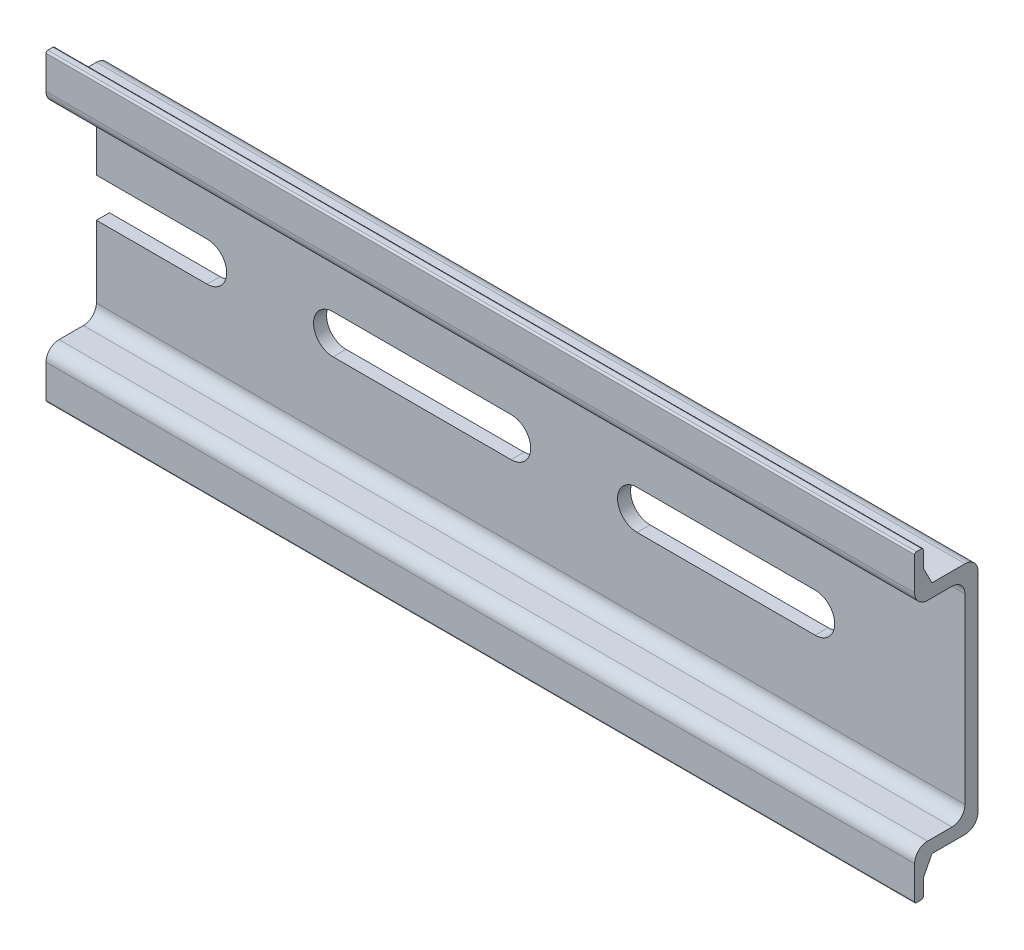
SolidWorks part; units mm, degrees
ref_plane "Front Plane" through (0, 0, 0) normal (0, 0, 1) x (1, 0, 0)
ref_plane "Top Plane" through (0, 0, 0) normal (0, 1, 0) x (1, 0, 0)
ref_plane "Right Plane" through (0, 0, 0) normal (1, 0, 0) x (0, 0, -1)
sketch "Sketch1" plane through (0, 0, 0) normal (1, 0, 0) x (0, 0, -1)
  line L0 (-6.5, 17.5) -> (-7.1, 17.5)
  line L1 (-7.3, 17.3) -> (-7.3, 13.5)
  line L2 (-5.8, 12) -> (-3, 12)
  line L3 (-1.5, 10.5) -> (-1.5, -10.5)
  line L4 (-5.8, -12) -> (-3, -12)
  line L5 (-6.3, -15.4626) -> (-6.3, -17.3)
  line L6 (-5.3, -13.5) -> (-6.3, -15.4626)
  line L7 (-1.5, -13.5) -> (-5.3, -13.5)
  line L8 (-7.3, -17.3) -> (-7.3, -13.5)
  line L9 (-6.5, -17.5) -> (-7.1, -17.5)
  line L10 (0, -12) -> (0, 12)
  line L11 (-1.5, 13.5) -> (-5.3, 13.5)
  line L12 (-5.3, 13.5) -> (-6.3, 15.4626)
  line L13 (-6.3, 15.4626) -> (-6.3, 17.3)
  line L14 (0, 0) -> (-7.3, 0) construction
  arc A0 (-6.3, 17.3) -> (-6.5, 17.5) centre (-6.5, 17.3) ccw
  arc A1 (-7.1, 17.5) -> (-7.3, 17.3) centre (-7.1, 17.3) ccw
  arc A2 (-7.3, 13.5) -> (-5.8, 12) centre (-5.8, 13.5) ccw
  arc A3 (-1.5, 10.5) -> (-3, 12) centre (-3, 10.5) ccw
  arc A4 (-1.5, -10.5) -> (-3, -12) centre (-3, -10.5) cw
  arc A5 (0, -12) -> (-1.5, -13.5) centre (-1.5, -12) cw
  arc A6 (-7.3, -13.5) -> (-5.8, -12) centre (-5.8, -13.5) cw
  arc A7 (-7.1, -17.5) -> (-7.3, -17.3) centre (-7.1, -17.3) cw
  arc A8 (-6.3, -17.3) -> (-6.5, -17.5) centre (-6.5, -17.3) cw
  arc A9 (0, 12) -> (-1.5, 13.5) centre (-1.5, 12) ccw
  dimension "FIX_9" = 1.5
  dimension "FIX_10" = 1.5
  dimension "FIX_11" = 0.2
  dimension "FIX_12" = 0.2
  dimension "FIX_13" = 1.5
  dimension "FIX_1" = 35
  dimension "FIX_2" = 24
  dimension "FIX_3" = 7.3
  dimension "FIX_4" = 27
  dimension "FIX_5" = 1
  dimension "FIX_6" = 5.3
  dimension "FIX_7" = 117
  dimension "FIX_8" = 1.5
extrude "Boss-Extrude1" add sketch "Sketch1" along normal blind 100
ref_plane "Plane1" through (100, 0, 0) normal (1, 0, 0) x (0, 0, -1)
sketch "Sketch2" plane through (0, 0, 0) normal (0, 0, 1) x (1, 0, 0)
  line L0 (62.25, 0) -> (82.75, 0) construction
  line L1 (62.25, 2.25) -> (82.75, 2.25)
  line L2 (62.25, -2.25) -> (82.75, -2.25)
  line L3 (85, 0) -> (60, 0) construction
  line L4 (100, -4.015) -> (100, 4.015) construction
  arc A0 (62.25, 2.25) -> (62.25, -2.25) centre (62.25, 0) ccw
  arc A1 (82.75, -2.25) -> (82.75, 2.25) centre (82.75, 0) ccw
  point P2 (72.5, 0)
  dimension "FIX_14" = 15
  dimension "FIX_15" = 25
  dimension "FIX_16" = 4.5
extrude "Cut-Extrude1" cut sketch "Sketch2" along normal through all
pattern_linear "LPattern1" count 3 spacing 35 along (-1, 0, 0) of "Cut-Extrude1"
equation "\"KSS_1@LPattern1\"=\"L@Boss-Extrude1\" / 35"
